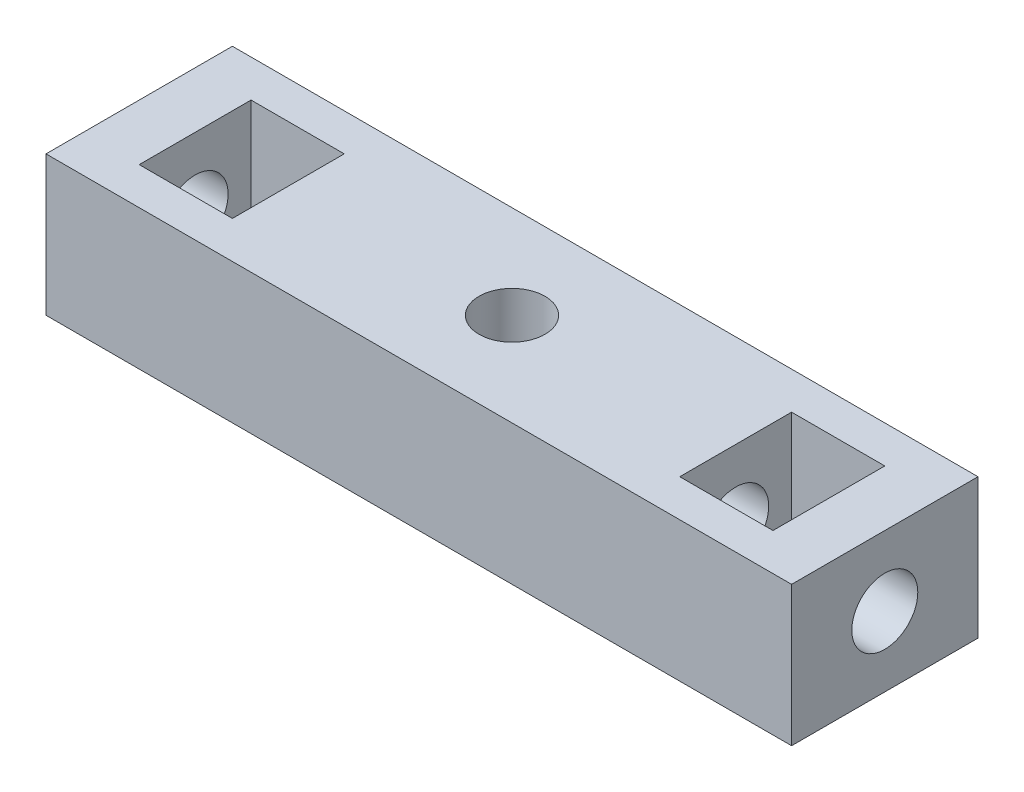
SolidWorks part; units mm, degrees
ref_plane "Front Plane" through (0, 0, 0) normal (0, 0, 1) x (1, 0, 0)
ref_plane "Top Plane" through (0, 0, 0) normal (0, 1, 0) x (1, 0, 0)
ref_plane "Right Plane" through (0, 0, 0) normal (1, 0, 0) x (0, 0, -1)
sketch "Sketch1" plane through (0, 0, 0) normal (0, 1, 0) x (1, 0, 0)
  line L1 (-25.4, -63.5) -> (25.4, -63.5)
  line L2 (-25.4, -63.5) -> (-25.4, 63.5)
  line L3 (-25.4, 63.5) -> (25.4, 63.5)
  line L4 (25.4, -63.5) -> (25.4, 63.5)
  line L5 (-25.4, -63.5) -> (25.4, 63.5) construction
  line L6 (-25.4, 63.5) -> (25.4, -63.5) construction
  point P0 (0, 0)
  dimension "D1" = 127
  dimension "D2" = 50.8
extrude "Boss-Extrude1" add sketch "Sketch1" along normal blind 9.525
sketch "Sketch2" plane through (0, 9.525, 0) normal (0, 1, 0) x (1, 0, 0)
  line L0 (25.4, -63.5) -> (25.4, 63.5) construction
  line L1 (-25.4, -101.6) -> (25.4, -101.6)
  line L2 (-25.4, -101.6) -> (-25.4, 50.8)
  line L3 (-25.4, 50.8) -> (25.4, 50.8)
  line L4 (25.4, -101.6) -> (25.4, 50.8)
  line L5 (-25.4, -101.6) -> (25.4, 50.8) construction
  line L6 (-25.4, 50.8) -> (25.4, -101.6) construction
  line L7 (-25.4, 63.5) -> (-25.4, -63.5) construction
  line L8 (25.4, 63.5) -> (-25.4, 63.5) construction
  point P0 (0, -25.4)
  dimension "D1" = 152.4
  dimension "D2" = 12.7
extrude "Cut-Extrude1" cut sketch "Sketch2" against normal through all
sketch "Sketch3" plane through (0, 0, -63.5) normal (0, 0, -1) x (-1, 0, 0)
  point P0 (22.225, -13.7665)
  point P3 (-22.225, -13.7665)
sketch "Sketch4" plane through (0, 9.525, 0) normal (0, 1, 0) x (1, 0, 0)
  point P0 (0, 57.15)
hole_wizard "#8 Clearance Hole1" positions "Sketch4" profile "Sketch5" hole size "#8" standard "ANSI Inch" end condition through all
sketch "Sketch5" plane through (0, 9.525, -57.15) normal (1, 0, 0) x (0, 0, 1)
  line L0 (0, 0) -> (0, 9.525)
  line L1 (0, 9.525) -> (2.2479, 9.525)
  line L2 (2.2479, 9.525) -> (2.2479, 0)
  line L5 (2.2479, 0) -> (0, 0)
  line L11 (0, -6.35) -> (0, 107.95) construction
  dimension "Thru Hole Dia." = 4.4958
  dimension "Thru Hole Depth" = 9.525
sketch "Sketch6" plane through (-25.4, 0, 0) normal (-1, 0, 0) x (0, 0, 1)
  point P0 (-57.15, 4.7625)
hole_wizard "#8 Clearance Hole2" positions "Sketch6" profile "Sketch8" hole size "#8" standard "ANSI Inch"
sketch "Sketch8" plane through (-25.4, 4.7625, -57.15) normal (0, 1, 0) x (0, 0, 1)
  line L0 (0, 0) -> (0, 15.3207)
  line L1 (0, 15.3207) -> (2.2479, 13.97)
  line L2 (2.2479, 13.97) -> (2.2479, 0)
  line L5 (2.2479, 0) -> (0, 0)
  line L10 (0, 15.3207) -> (-2.2479, 13.97) construction
  line L11 (0, -6.35) -> (0, 107.95) construction
  dimension "Hole Dia." = 4.4958
  dimension "Hole Depth" = 13.97
  dimension "Drill Angle" = 118
sketch "Sketch9" plane through (25.4, 0, 0) normal (1, 0, 0) x (0, 0, -1)
sketch "Sketch11" plane through (25.4, 0, 0) normal (1, 0, 0) x (0, 0, -1)
  point P0 (57.15, 4.7625)
hole_wizard "#8 Clearance Hole3" positions "Sketch11" profile "Sketch10" hole size "#8" standard "ANSI Inch"
sketch "Sketch10" plane through (25.4, 4.7625, -57.15) normal (0, 1, 0) x (0, 0, -1)
  line L0 (0, 0) -> (0, 15.3207)
  line L1 (0, 15.3207) -> (2.2479, 13.97)
  line L2 (2.2479, 13.97) -> (2.2479, 0)
  line L5 (2.2479, 0) -> (0, 0)
  line L10 (0, 15.3207) -> (-2.2479, 13.97) construction
  line L11 (0, -6.35) -> (0, 107.95) construction
  dimension "Hole Dia." = 4.4958
  dimension "Hole Depth" = 13.97
  dimension "Drill Angle" = 118
sketch "Sketch12" plane through (0, 9.525, 0) normal (0, 1, 0) x (1, 0, 0)
  line L0 (-25.4, 63.5) -> (-25.4, 50.8) construction
  line L1 (-21.59, 53.34) -> (-15.24, 53.34)
  line L2 (-21.59, 53.34) -> (-21.59, 60.96)
  line L3 (-21.59, 60.96) -> (-15.24, 60.96)
  line L4 (-15.24, 53.34) -> (-15.24, 60.96)
  line L5 (-21.59, 53.34) -> (-15.24, 60.96) construction
  line L6 (-21.59, 60.96) -> (-15.24, 53.34) construction
  line L7 (25.4, 50.8) -> (25.4, 63.5) construction
  line L8 (15.24, 53.34) -> (21.59, 53.34)
  line L9 (15.24, 53.34) -> (15.24, 60.96)
  line L10 (15.24, 60.96) -> (21.59, 60.96)
  line L11 (21.59, 53.34) -> (21.59, 60.96)
  line L12 (15.24, 53.34) -> (21.59, 60.96) construction
  line L13 (15.24, 60.96) -> (21.59, 53.34) construction
  point P0 (-18.415, 57.15)
  point P8 (-25.4, 57.15)
  point P9 (18.415, 57.15)
  point P15 (0, 0)
  dimension "D1" = 6.35
  dimension "D2" = 7.62
  dimension "D3" = 3.81
  dimension "D4" = 6.35
  dimension ".15" = 3.81
extrude "Cut-Extrude2" cut sketch "Sketch12" against normal through all
